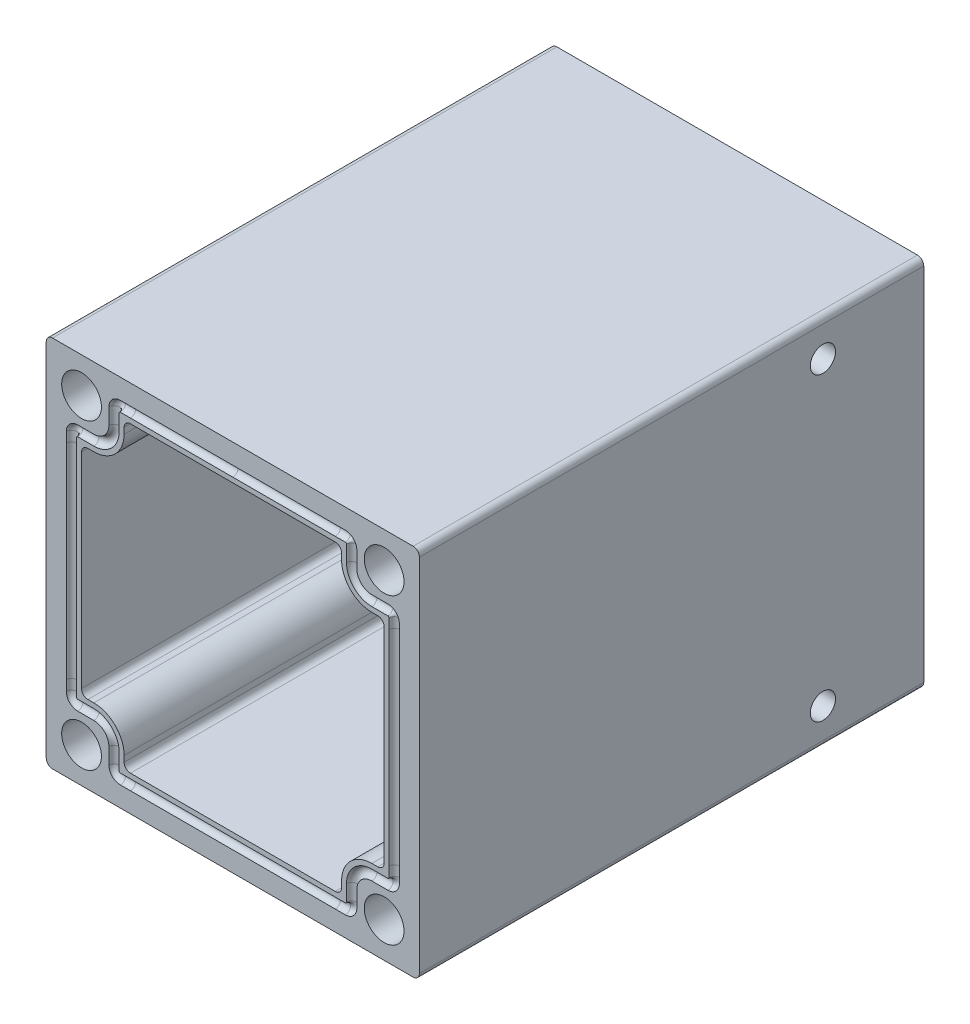
SolidWorks part; units mm, degrees
ref_plane "Front Plane" through (0, 0, 0) normal (0, 0, 1) x (1, 0, 0)
ref_plane "Top Plane" through (0, 0, 0) normal (0, 1, 0) x (1, 0, 0)
ref_plane "Right Plane" through (0, 0, 0) normal (1, 0, 0) x (0, 0, -1)
sketch "Sketch1" plane through (0, 0, 0) normal (0, 0, 1) x (1, 0, 0)
  line L9 (23.495, 22.7012) -> (23.495, -22.7012)
  line L14 (22.7012, -23.495) -> (-22.7012, -23.495)
  line L15 (-23.495, -22.7012) -> (-23.495, 22.7012)
  line L16 (-22.7012, 23.495) -> (22.7012, 23.495)
  line L28 (-20.32, -12.8968) -> (-20.32, -14.1668) construction
  line L34 (-14.1669, -20.32) -> (-12.8969, -20.32) construction
  line L51 (-12.8969, -20.32) -> (12.8968, -20.32) construction
  line L54 (20.32, -12.8969) -> (20.32, 12.8968) construction
  line L57 (12.8969, 20.32) -> (-12.8968, 20.32) construction
  line L60 (-20.32, 12.8969) -> (-20.32, -12.8968) construction
  line L63 (-19.5262, -14.9606) -> (-17.5006, -14.9606) construction
  line L64 (-12.8969, -19.05) -> (12.8968, -19.05)
  line L65 (-13.6906, 18.2563) -> (-13.6906, 17.5006)
  line L66 (-17.5006, 13.6906) -> (-18.2562, 13.6906)
  line L67 (18.2563, 13.6906) -> (17.5006, 13.6906)
  line L68 (13.6906, 17.5006) -> (13.6906, 18.2562)
  line L69 (13.6906, -18.2563) -> (13.6906, -17.5006)
  line L70 (17.5006, -13.6906) -> (18.2562, -13.6906)
  line L71 (-14.9606, -17.5006) -> (-14.9606, -19.5262) construction
  line L73 (-12.8968, 20.32) -> (-14.1668, 20.32) construction
  line L74 (-14.9606, 19.5262) -> (-14.9606, 17.5006) construction
  line L75 (-17.5006, 14.9606) -> (-19.5262, 14.9606) construction
  line L76 (-20.32, 14.1669) -> (-20.32, 12.8969) construction
  line L77 (20.32, 12.8968) -> (20.32, 14.1668) construction
  line L78 (19.5263, 14.9606) -> (17.5006, 14.9606) construction
  line L79 (14.9606, 17.5006) -> (14.9606, 19.5262) construction
  line L80 (14.1669, 20.32) -> (12.8969, 20.32) construction
  line L81 (12.8968, -20.32) -> (14.1668, -20.32) construction
  line L82 (14.9606, -19.5263) -> (14.9606, -17.5006) construction
  line L83 (17.5006, -14.9606) -> (19.5262, -14.9606) construction
  line L84 (20.32, -14.1669) -> (20.32, -12.8969) construction
  line L85 (-18.2563, -13.6906) -> (-17.5006, -13.6906)
  line L86 (-13.6906, -17.5006) -> (-13.6906, -18.2562)
  line L90 (19.05, -12.8969) -> (19.05, 12.8968)
  line L93 (12.8969, 19.05) -> (-12.8968, 19.05)
  line L97 (-19.05, 12.8969) -> (-19.05, -12.8968)
  circle A0 centre (0, 0) radius 19.05 construction
  circle A13 centre (-19.05, -19.05) radius 2.5019 construction
  circle A14 centre (-19.05, 19.05) radius 2.5019 construction
  circle A15 centre (19.05, 19.05) radius 2.5019 construction
  circle A16 centre (19.05, -19.05) radius 2.5019 construction
  circle A17 centre (19.05, -19.05) radius 4.0894 construction
  arc A50 (-13.6906, -17.5006) -> (-17.5006, -13.6906) centre (-17.5006, -17.5006) ccw
  arc A51 (-12.8969, -19.05) -> (-13.6906, -18.2562) centre (-12.8969, -18.2562) cw
  arc A52 (-18.2563, -13.6906) -> (-19.05, -12.8968) centre (-18.2563, -12.8968) cw
  arc A53 (-13.6906, 18.2563) -> (-12.8968, 19.05) centre (-12.8968, 18.2563) cw
  arc A54 (-17.5006, 13.6906) -> (-13.6906, 17.5006) centre (-17.5006, 17.5006) ccw
  arc A55 (-19.05, 12.8969) -> (-18.2562, 13.6906) centre (-18.2562, 12.8969) cw
  arc A56 (18.2563, 13.6906) -> (19.05, 12.8968) centre (18.2563, 12.8968) cw
  arc A57 (13.6906, 17.5006) -> (17.5006, 13.6906) centre (17.5006, 17.5006) ccw
  arc A58 (12.8969, 19.05) -> (13.6906, 18.2562) centre (12.8969, 18.2562) cw
  arc A59 (13.6906, -18.2563) -> (12.8968, -19.05) centre (12.8968, -18.2563) cw
  arc A60 (17.5006, -13.6906) -> (13.6906, -17.5006) centre (17.5006, -17.5006) ccw
  arc A61 (19.05, -12.8969) -> (18.2562, -13.6906) centre (18.2562, -12.8969) cw
  arc A62 (-14.9606, -17.5006) -> (-17.5006, -14.9606) centre (-17.5006, -17.5006) ccw construction
  arc A63 (-14.1669, -20.32) -> (-14.9606, -19.5262) centre (-14.1669, -19.5262) cw construction
  arc A64 (-20.32, -14.1668) -> (-19.5262, -14.9606) centre (-19.5262, -14.1668) ccw construction
  arc A65 (-14.1668, 20.32) -> (-14.9606, 19.5262) centre (-14.1668, 19.5262) ccw construction
  arc A66 (-17.5006, 14.9606) -> (-14.9606, 17.5006) centre (-17.5006, 17.5006) ccw construction
  arc A67 (-20.32, 14.1669) -> (-19.5262, 14.9606) centre (-19.5262, 14.1669) cw construction
  arc A68 (20.32, 14.1668) -> (19.5263, 14.9606) centre (19.5263, 14.1668) ccw construction
  arc A69 (14.9606, 17.5006) -> (17.5006, 14.9606) centre (17.5006, 17.5006) ccw construction
  arc A70 (14.1669, 20.32) -> (14.9606, 19.5262) centre (14.1669, 19.5262) cw construction
  arc A71 (14.1668, -20.32) -> (14.9606, -19.5263) centre (14.1668, -19.5263) ccw construction
  arc A72 (17.5006, -14.9606) -> (14.9606, -17.5006) centre (17.5006, -17.5006) ccw construction
  arc A73 (20.32, -14.1669) -> (19.5262, -14.9606) centre (19.5262, -14.1669) cw construction
  arc A74 (-22.7012, -23.495) -> (-23.495, -22.7012) centre (-22.7013, -22.7013) cw
  arc A75 (22.7012, -23.495) -> (23.495, -22.7012) centre (22.7012, -22.7012) ccw
  arc A76 (23.495, 22.7012) -> (22.7012, 23.495) centre (22.7012, 22.7013) ccw
  arc A77 (-23.495, 22.7012) -> (-22.7012, 23.495) centre (-22.7013, 22.7012) cw
  point P29 (0, 0)
  point P32 (0, 0)
  point P33 (0, 0)
  point P42 (0, 0)
  point P45 (19.05, -14.9606)
  point P57 (14.9606, -19.05)
  point P82 (0, 0)
  point P89 (0, 0)
  point P140 (0, 0)
  dimension "D1" = 38.1
  dimension "D2" = 3.175
  dimension "D3" = 3.175
  dimension "D5" = 4
  dimension "D6" = 1.5875
  dimension "D8" = 5.0038
  dimension "D9" = 0.7937
  dimension "D7" = 3.81
  dimension "D4" = 2.54
  dimension "D14" = 0.7937
  dimension "D11" = 0.7937
  dimension "D12" = 3.175
  dimension "D13" = 3.175
  dimension "D15" = 4
  dimension "D10" = 4
extrude "Boss-Extrude1" add sketch "Sketch1" against normal blind 63.5
sketch "Sketch4" [suppressed] plane through (0, 0, 0) normal (1, 0, 0) x (0, 0, -1)
  line L0 (0, 38.1462) -> (65.278, 38.1462) construction
  line L3 (0, 0) -> (65.278, 0) construction
  line L5 (0, -29.86) -> (65.278, -29.86) construction
  line L6 (0, 52.7974) -> (0, 23.495) construction
  line L7 (65.278, 52.7974) -> (65.278, 23.495) construction
  line L8 (0, -36.225) -> (0, -23.495) construction
  line L9 (65.278, -36.225) -> (65.278, -23.495) construction
  line L10 (65.278, -23.495) -> (65.278, 23.495) construction
  circle A0 centre (12.7, 38.1306) radius 3.9688
  circle A1 centre (52.578, 38.1306) radius 3.9687
  circle A2 centre (10.6423, -36.7905) radius 3.9688
  circle A3 centre (54.6357, -36.7905) radius 3.9687
  dimension "D1" = 12.7
  dimension "D3" = 7.9375
  dimension "D4" = 7.9375
  dimension "D2" = 12.7
  dimension "D5" = 12.7
  dimension "D6" = 12.7
extrude "Cut-Extrude2" [suppressed] cut sketch "Sketch4" along normal through all contours A1 | A0 | A3 | A2
sketch "Sketch7" plane through (0, 0, 0) normal (1, 0, 0) x (0, 0, -1)
  circle A0 centre (0, 20.32) radius 0.65
  dimension "D1" = 1.3
sketch "Sketch11" plane through (0, 0, 0) normal (0, 0, 1) x (1, 0, 0)
  line L0 (-14.9606, 19.5262) -> (-14.9606, 17.5006) construction
  line L1 (-12.8968, 20.32) -> (-14.1668, 20.32) construction
  line L2 (12.8969, 20.32) -> (-12.8968, 20.32) construction
  line L3 (14.1669, 20.32) -> (12.8969, 20.32) construction
  line L4 (14.9606, 17.5006) -> (14.9606, 19.5262) construction
  line L5 (19.5263, 14.9606) -> (17.5006, 14.9606) construction
  line L6 (20.32, 12.8968) -> (20.32, 14.1668) construction
  line L7 (20.32, -12.8969) -> (20.32, 12.8968) construction
  line L8 (20.32, -14.1669) -> (20.32, -12.8969) construction
  line L9 (17.5006, -14.9606) -> (19.5262, -14.9606) construction
  line L10 (14.9606, -19.5263) -> (14.9606, -17.5006) construction
  line L11 (12.8968, -20.32) -> (14.1668, -20.32) construction
  line L12 (-12.8969, -20.32) -> (12.8968, -20.32) construction
  line L13 (-14.1669, -20.32) -> (-12.8969, -20.32) construction
  line L14 (-14.9606, -17.5006) -> (-14.9606, -19.5262) construction
  line L15 (-19.5262, -14.9606) -> (-17.5006, -14.9606) construction
  line L16 (-20.32, -12.8968) -> (-20.32, -14.1668) construction
  line L17 (-20.32, 12.8969) -> (-20.32, -12.8968) construction
  line L18 (-20.32, 14.1669) -> (-20.32, 12.8969) construction
  line L19 (-17.5006, 14.9606) -> (-19.5262, 14.9606) construction
  line L20 (-14.9606, 19.5262) -> (-14.9606, 17.5006)
  line L21 (-12.8968, 20.32) -> (-14.1668, 20.32)
  line L22 (12.8969, 20.32) -> (-12.8968, 20.32)
  line L23 (14.1669, 20.32) -> (12.8969, 20.32)
  line L24 (14.9606, 17.5006) -> (14.9606, 19.5262)
  line L25 (19.5263, 14.9606) -> (17.5006, 14.9606)
  line L26 (20.32, 12.8968) -> (20.32, 14.1668)
  line L27 (20.32, -12.8969) -> (20.32, 12.8968)
  line L28 (20.32, -14.1669) -> (20.32, -12.8969)
  line L29 (17.5006, -14.9606) -> (19.5262, -14.9606)
  line L30 (14.9606, -19.5263) -> (14.9606, -17.5006)
  line L31 (12.8968, -20.32) -> (14.1668, -20.32)
  line L32 (-12.8969, -20.32) -> (12.8968, -20.32)
  line L33 (-14.1669, -20.32) -> (-12.8969, -20.32)
  line L34 (-14.9606, -17.5006) -> (-14.9606, -19.5262)
  line L35 (-19.5262, -14.9606) -> (-17.5006, -14.9606)
  line L36 (-20.32, -12.8968) -> (-20.32, -14.1668)
  line L37 (-20.32, 12.8969) -> (-20.32, -12.8968)
  line L38 (-20.32, 14.1669) -> (-20.32, 12.8969)
  line L39 (-17.5006, 14.9606) -> (-19.5262, 14.9606)
  arc A0 (-14.1668, 20.32) -> (-14.9606, 19.5262) centre (-14.1668, 19.5262) ccw construction
  arc A1 (14.9606, 19.5262) -> (14.1669, 20.32) centre (14.1669, 19.5262) ccw construction
  arc A2 (14.9606, 17.5006) -> (17.5006, 14.9606) centre (17.5006, 17.5006) ccw construction
  arc A3 (20.32, 14.1668) -> (19.5263, 14.9606) centre (19.5263, 14.1668) ccw construction
  arc A4 (19.5262, -14.9606) -> (20.32, -14.1669) centre (19.5262, -14.1669) ccw construction
  arc A5 (17.5006, -14.9606) -> (14.9606, -17.5006) centre (17.5006, -17.5006) ccw construction
  arc A6 (14.1668, -20.32) -> (14.9606, -19.5263) centre (14.1668, -19.5263) ccw construction
  arc A7 (-14.9606, -19.5262) -> (-14.1669, -20.32) centre (-14.1669, -19.5262) ccw construction
  arc A8 (-14.9606, -17.5006) -> (-17.5006, -14.9606) centre (-17.5006, -17.5006) ccw construction
  arc A9 (-20.32, -14.1668) -> (-19.5262, -14.9606) centre (-19.5262, -14.1668) ccw construction
  arc A10 (-19.5262, 14.9606) -> (-20.32, 14.1669) centre (-19.5262, 14.1669) ccw construction
  arc A11 (-17.5006, 14.9606) -> (-14.9606, 17.5006) centre (-17.5006, 17.5006) ccw construction
  arc A12 (-14.1668, 20.32) -> (-14.9606, 19.5262) centre (-14.1668, 19.5262) ccw
  arc A13 (14.9606, 19.5262) -> (14.1669, 20.32) centre (14.1669, 19.5262) ccw
  arc A14 (14.9606, 17.5006) -> (17.5006, 14.9606) centre (17.5006, 17.5006) ccw
  arc A15 (20.32, 14.1668) -> (19.5263, 14.9606) centre (19.5263, 14.1668) ccw
  arc A16 (19.5262, -14.9606) -> (20.32, -14.1669) centre (19.5262, -14.1669) ccw
  arc A17 (17.5006, -14.9606) -> (14.9606, -17.5006) centre (17.5006, -17.5006) ccw
  arc A18 (14.1668, -20.32) -> (14.9606, -19.5263) centre (14.1668, -19.5263) ccw
  arc A19 (-14.9606, -19.5262) -> (-14.1669, -20.32) centre (-14.1669, -19.5262) ccw
  arc A20 (-14.9606, -17.5006) -> (-17.5006, -14.9606) centre (-17.5006, -17.5006) ccw
  arc A21 (-20.32, -14.1668) -> (-19.5262, -14.9606) centre (-19.5262, -14.1668) ccw
  arc A22 (-19.5262, 14.9606) -> (-20.32, 14.1669) centre (-19.5262, 14.1669) ccw
  arc A23 (-17.5006, 14.9606) -> (-14.9606, 17.5006) centre (-17.5006, 17.5006) ccw
sweep "Cut-Sweep2" cut profiles "Sketch7" path "Sketch11"
sketch "Sketch10" plane through (0, 0, 0) normal (0, 0, 1) x (1, 0, 0)
  circle A0 centre (19.05, 19.05) radius 2.5019 construction
  circle A1 centre (19.05, -19.05) radius 2.5019 construction
  circle A2 centre (-19.05, -19.05) radius 2.5019 construction
  circle A3 centre (-19.05, 19.05) radius 2.5019 construction
  circle A4 centre (19.05, 19.05) radius 2.5019
  circle A5 centre (19.05, -19.05) radius 2.5019
  circle A6 centre (-19.05, -19.05) radius 2.5019
  circle A7 centre (-19.05, 19.05) radius 2.5019
extrude "Cut-Extrude3" cut sketch "Sketch10" against normal blind 12.7
sketch "Sketch12" plane through (0, 0, 0) normal (0, 0, 1) x (1, 0, 0)
  line L0 (23.495, 22.7012) -> (23.495, -22.7012) construction
  line L1 (22.7012, -23.495) -> (-22.7012, -23.495) construction
  line L2 (-23.495, -22.7012) -> (-23.495, 22.7012) construction
  line L3 (-22.7012, 23.495) -> (22.7012, 23.495) construction
  line L4 (23.495, 22.7012) -> (23.495, -22.7012)
  line L5 (22.7012, -23.495) -> (-22.7012, -23.495)
  line L6 (-23.495, -22.7012) -> (-23.495, 22.7012)
  line L7 (-22.7012, 23.495) -> (22.7012, 23.495)
  arc A0 (23.495, 22.7012) -> (22.7012, 23.495) centre (22.7012, 22.7013) ccw construction
  arc A1 (22.7012, -23.495) -> (23.495, -22.7012) centre (22.7012, -22.7012) ccw construction
  arc A2 (-23.495, -22.7012) -> (-22.7012, -23.495) centre (-22.7013, -22.7013) ccw construction
  arc A3 (-22.7012, 23.495) -> (-23.495, 22.7012) centre (-22.7013, 22.7012) ccw construction
  arc A4 (23.495, 22.7012) -> (22.7012, 23.495) centre (22.7012, 22.7013) ccw
  arc A5 (22.7012, -23.495) -> (23.495, -22.7012) centre (22.7012, -22.7012) ccw
  arc A6 (-23.495, -22.7012) -> (-22.7012, -23.495) centre (-22.7013, -22.7013) ccw
  arc A7 (-22.7012, 23.495) -> (-23.495, 22.7012) centre (-22.7013, 22.7012) ccw
  circle A8 centre (0, 0) radius 10.414
  dimension "D1" = 20.828
extrude "Boss-Extrude2" add sketch "Sketch12" along normal blind 3.175 from surface at -63.5 starting at face at (0, 0, -63.5)
sketch "Sketch13" plane through (23.495, 0, 0) normal (1, 0, 0) x (0, 0, -1)
  line L0 (0, 0) -> (63.5, 0)
  line L1 (0, 22.7012) -> (0, -22.7012) construction
  line L2 (63.5, 22.7012) -> (63.5, -22.7012) construction
  line L3 (31.75, 22.7012) -> (31.75, -22.7012)
  line L4 (63.5, 22.7012) -> (0, 22.7012) construction
  line L5 (63.5, -22.7012) -> (0, -22.7012) construction
sketch "Sketch14" plane through (23.495, 0, 0) normal (1, 0, 0) x (0, 0, -1)
  line L0 (63.5, 22.7012) -> (63.5, -22.7012) construction
  line L1 (63.5, 23.495) -> (0, 23.495) construction
  line L2 (63.5, -23.495) -> (0, -23.495) construction
  circle A0 centre (50.8, 18.923) radius 1.5875
  circle A1 centre (50.8, -18.923) radius 1.5875
  dimension "D3" = 3.175
  dimension "D4" = 3.175
  dimension "D1" = 12.7
  dimension "D2" = 12.7
  dimension "D5" = 4.572
  dimension "D6" = 4.572
extrude "Cut-Extrude4" cut sketch "Sketch14" against normal blind 6.35
